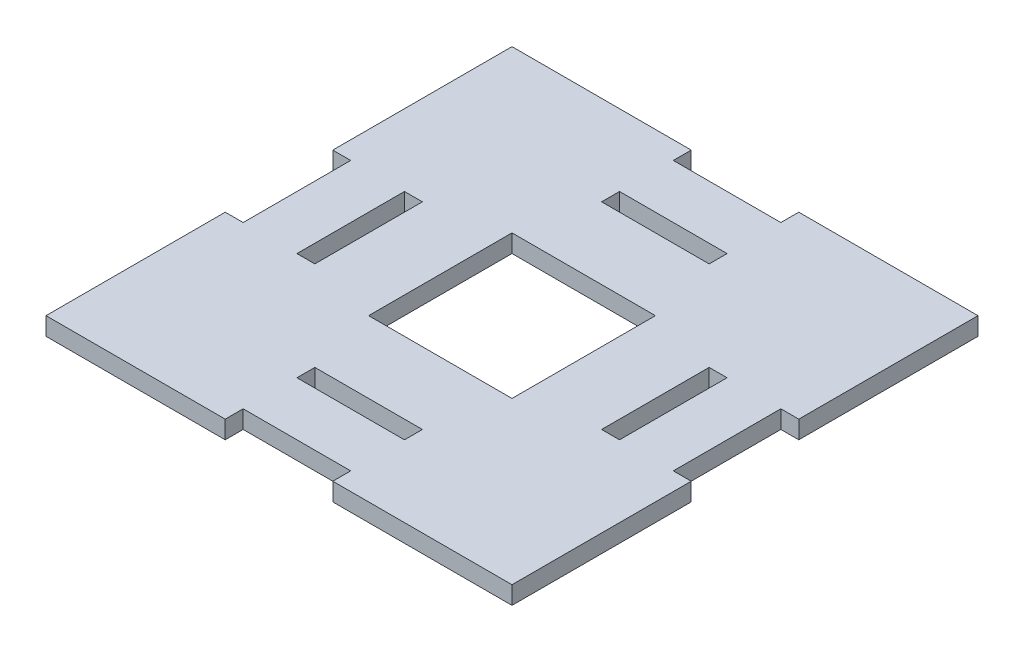
SolidWorks part; units mm, degrees
ref_plane "Front Plane" through (0, 0, 0) normal (0, 0, 1) x (1, 0, 0)
ref_plane "Top Plane" through (0, 0, 0) normal (0, 1, 0) x (1, 0, 0)
ref_plane "Right Plane" through (0, 0, 0) normal (1, 0, 0) x (0, 0, -1)
sketch "Sketch1" plane through (0, 0, 0) normal (0, 1, 0) x (1, 0, 0)
  line L1 (0, 0) -> (82.55, 0)
  line L2 (0, 0) -> (0, 82.55)
  line L3 (0, 82.55) -> (82.55, 82.55)
  line L4 (82.55, 0) -> (82.55, 82.55)
  dimension "D1" = 82.55
  dimension "D2" = 82.55
extrude "Boss-Extrude1" add sketch "Sketch1" along normal blind 3.175
sketch "Sketch2" plane through (0, 3.175, 0) normal (0, 1, 0) x (1, 0, 0)
  line L0 (82.55, 82.55) -> (0, 82.55) construction
  line L1 (28.575, 53.975) -> (53.975, 53.975)
  line L2 (28.575, 53.975) -> (28.575, 28.575)
  line L3 (28.575, 28.575) -> (53.975, 28.575)
  line L4 (53.975, 53.975) -> (53.975, 28.575)
  line L5 (31.75, 69.85) -> (50.8, 69.85)
  line L6 (31.75, 69.85) -> (31.75, 66.675)
  line L7 (31.75, 66.675) -> (50.8, 66.675)
  line L8 (50.8, 69.85) -> (50.8, 66.675)
  line L9 (12.7, 50.8) -> (15.875, 50.8)
  line L10 (12.7, 50.8) -> (12.7, 31.75)
  line L11 (12.7, 31.75) -> (15.875, 31.75)
  line L12 (15.875, 50.8) -> (15.875, 31.75)
  line L13 (82.55, 0) -> (82.55, 82.55) construction
  line L14 (-1.7463, 0) -> (1.7463, 0) construction
  line L15 (41.275, 82.55) -> (41.275, 0) construction
  line L16 (0, 41.275) -> (82.55, 41.275) construction
  line L17 (66.675, 50.8) -> (66.675, 31.75)
  line L18 (69.85, 31.75) -> (66.675, 31.75)
  line L19 (69.85, 50.8) -> (69.85, 31.75)
  line L20 (69.85, 50.8) -> (66.675, 50.8)
  line L21 (50.8, 12.7) -> (50.8, 15.875)
  line L22 (31.75, 15.875) -> (50.8, 15.875)
  line L23 (31.75, 12.7) -> (31.75, 15.875)
  line L24 (31.75, 12.7) -> (50.8, 12.7)
  line L25 (0, -1.7463) -> (0, 1.7463) construction
  point P28 (41.275, 41.275)
  point P29 (41.275, 53.975)
  point P34 (53.975, 41.275)
  dimension "D1" = 19.05
  dimension "D2" = 3.175
  dimension "D3" = 3.175
  dimension "D4" = 19.05
  dimension "D5" = 25.4
  dimension "D6" = 25.4
  dimension "D9" = 9.525
  dimension "D10" = 9.525
  dimension "D11" = 25.4
  dimension "D12" = 25.4
extrude "Cut-Extrude1" cut sketch "Sketch2" against normal blind 3.175
sketch "Sketch3" plane through (0, 3.175, 0) normal (0, 1, 0) x (1, 0, 0)
  line L0 (82.55, 82.55) -> (0, 82.55) construction
  line L1 (31.75, 82.55) -> (50.8, 82.55)
  line L2 (31.75, 82.55) -> (31.75, 79.375)
  line L3 (31.75, 79.375) -> (50.8, 79.375)
  line L4 (50.8, 82.55) -> (50.8, 79.375)
  line L5 (82.55, 0) -> (82.55, 82.55) construction
  line L6 (0, 41.275) -> (82.55, 41.275) construction
  line L8 (41.275, 82.55) -> (41.275, 0) construction
  line L10 (79.375, 50.8) -> (79.375, 31.75)
  line L11 (82.55, 31.75) -> (79.375, 31.75)
  line L12 (82.55, 50.8) -> (82.55, 31.75)
  line L13 (82.55, 50.8) -> (79.375, 50.8)
  line L14 (50.8, 3.175) -> (31.75, 3.175)
  line L15 (31.75, 0) -> (31.75, 3.175)
  line L16 (50.8, 0) -> (31.75, 0)
  line L17 (50.8, 0) -> (50.8, 3.175)
  line L18 (3.175, 31.75) -> (3.175, 50.8)
  line L19 (0, 50.8) -> (3.175, 50.8)
  line L20 (0, 31.75) -> (0, 50.8)
  line L21 (0, 31.75) -> (3.175, 31.75)
  point P18 (41.275, 41.275)
  point P19 (41.275, 82.55)
  point P27 (82.55, 41.275)
  point P32 (41.275, 0)
  point P37 (0, 41.275)
  point P38 (41.275, 41.275)
  dimension "D1" = 3.175
  dimension "D2" = 19.05
  dimension "D3" = 31.75
  dimension "D4" = 4
extrude "Cut-Extrude2" cut sketch "Sketch3" against normal blind 3.175
